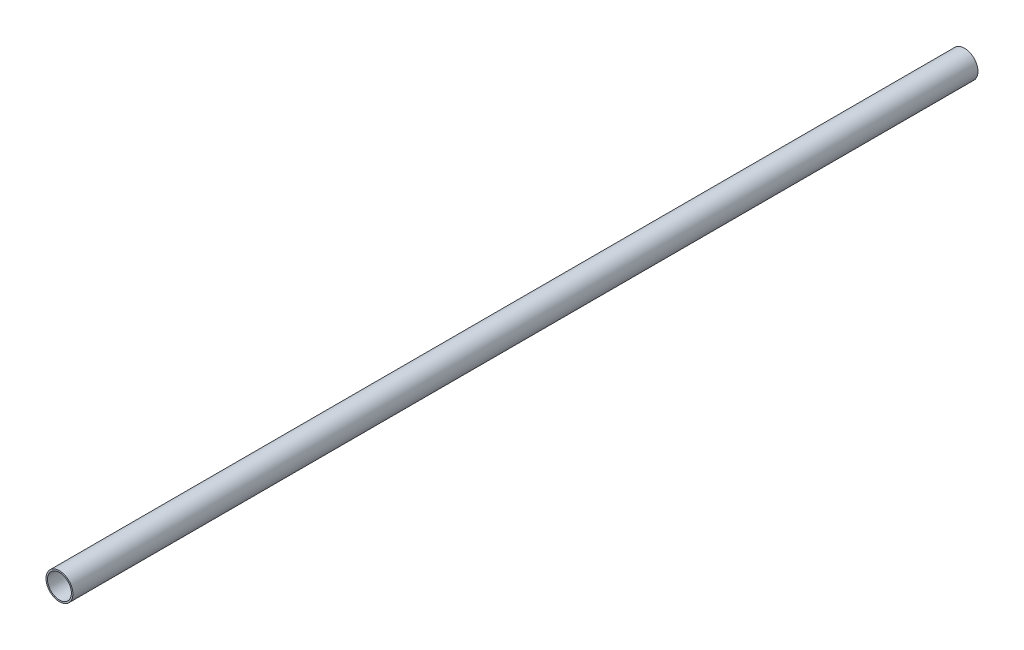
SolidWorks part; units mm, degrees
material "AISI 4130 Steel, annealed at 865C"
ref_plane "Front Plane" through (0, 0, 0) normal (0, 0, 1) x (1, 0, 0)
ref_plane "Top Plane" through (0, 0, 0) normal (0, 1, 0) x (1, 0, 0)
ref_plane "Right Plane" through (0, 0, 0) normal (1, 0, 0) x (0, 0, -1)
sketch "Sketch1" plane through (0, 0, 0) normal (0, 0, 1) x (1, 0, 0)
  circle A0 centre (0, 0) radius 7.9375
  circle A1 centre (0, 0) radius 7.0485
  dimension "D1" = 15.875
  dimension "D2" = 0.889
extrude "Boss-Extrude1" add sketch "Sketch1" along normal mid plane 533.4
equation "\"Torsion Bar Length\"= 21in"
equation "\"D1@Boss-Extrude1\"=\"Torsion Bar Length\""
